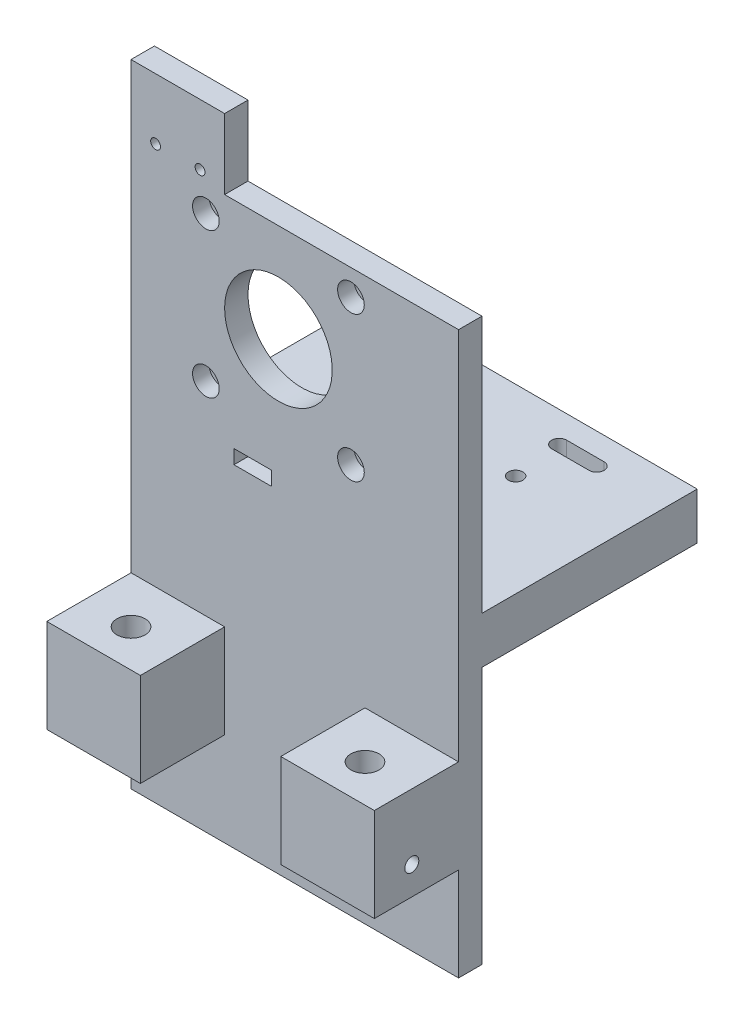
SolidWorks part; units mm, degrees
ref_plane "Front" through (0, 0, 0) normal (0, 0, 1) x (1, 0, 0)
ref_plane "Top" through (0, 0, 0) normal (0, 1, 0) x (1, 0, 0)
ref_plane "Right" through (0, 0, 0) normal (1, 0, 0) x (0, 0, -1)
sketch "Sketch1" plane through (0, 0, 0) normal (0, 0, 1) x (1, 0, 0)
  line L1 (-35, -60) -> (35, -60)
  line L2 (-35, -60) -> (-35, 60)
  line L3 (-35, 60) -> (35, 60)
  line L4 (35, -60) -> (35, 60)
  line L5 (-35, -60) -> (35, 60) construction
  line L6 (-35, 60) -> (35, -60) construction
  point P0 (0, 0)
  dimension "D1" = 120
  dimension "D2" = 70
extrude "Boss-Extrude1" add sketch "Sketch1" along normal blind 5
sketch "Sketch2" plane through (0, 0, 5) normal (0, 0, 1) x (1, 0, 0)
  line L0 (-35, 60) -> (-35, -60) construction
  line L1 (-35, -20) -> (-15, -20)
  line L2 (-35, -20) -> (-35, -40)
  line L3 (-35, -40) -> (-15, -40)
  line L4 (-15, -20) -> (-15, -40)
  line L5 (-35, -20) -> (-15, -40) construction
  line L6 (-35, -40) -> (-15, -20) construction
  line L7 (35, -60) -> (35, 60) construction
  line L8 (35, -20) -> (15, -20)
  line L9 (35, -20) -> (35, -40)
  line L10 (35, -40) -> (15, -40)
  line L11 (15, -20) -> (15, -40)
  line L12 (35, -20) -> (15, -40) construction
  line L13 (35, -40) -> (15, -20) construction
  point P4 (-25, -30)
  point P11 (25, -30)
  dimension "D1" = 20
  dimension "D2" = 20
  dimension "D3" = 20
  dimension "D4" = 20
  dimension "D5" = 40
extrude "Boss-Extrude2" add sketch "Sketch2" along normal blind 18
sketch "Sketch3" plane through (0, -20, 0) normal (0, 1, 0) x (1, 0, 0)
  line L0 (-25, -23) -> (-25, -5) construction
  line L1 (-15, -23) -> (-35, -23) construction
  line L2 (-15, -5) -> (-35, -5) construction
  line L3 (25, -23) -> (25, -5) construction
  line L4 (35, -23) -> (15, -23) construction
  line L5 (35, -5) -> (15, -5) construction
  circle A0 centre (-25, -15) radius 3
  circle A1 centre (25, -15) radius 3
  dimension "D1" = 6
  dimension "D2" = 6
  dimension "D3" = 10
  dimension "D4" = 10
extrude "Cut-Extrude1" cut sketch "Sketch3" against normal up to next
sketch "Sketch4" plane through (0, 0, 0) normal (0, 0, -1) x (-1, 0, 0)
  line L0 (-35, 60) -> (35, 60) construction
  line L1 (-12, 23.5) -> (19, 23.5) construction
  line L2 (-12, 23.5) -> (-12, 54.5) construction
  line L3 (-12, 54.5) -> (19, 54.5) construction
  line L4 (19, 23.5) -> (19, 54.5) construction
  line L5 (-12, 23.5) -> (19, 54.5) construction
  line L6 (-12, 54.5) -> (19, 23.5) construction
  line L7 (35, 60) -> (35, -60) construction
  circle A0 centre (3.5, 39) radius 11.5
  circle A1 centre (-12, 54.5) radius 1.55
  circle A2 centre (19, 54.5) radius 1.55
  circle A3 centre (19, 23.5) radius 1.55
  circle A4 centre (-12, 23.5) radius 1.55
  dimension "D1" = 23
  dimension "D3" = 3.1
  dimension "D4" = 3.1
  dimension "D5" = 3.1
  dimension "D6" = 3.1
  dimension "D2" = 31
  dimension "D7" = 21
  dimension "D8" = 31.5
extrude "Cut-Extrude2" cut sketch "Sketch4" against normal up to next
sketch "Sketch5" plane through (0, 0, 0) normal (0, 0, -1) x (-1, 0, 0)
  line L1 (35, 60) -> (15, 60)
  line L2 (35, 60) -> (35, 75)
  line L3 (35, 75) -> (15, 75)
  line L4 (15, 60) -> (15, 75)
  line L5 (35, 60) -> (15, 75) construction
  line L6 (35, 75) -> (15, 60) construction
  circle A0 centre (20.25, 62) radius 1.05
  circle A1 centre (29.75, 62) radius 1.05
  point P4 (25, 67.5)
  dimension "D3" = 2.1
  dimension "D4" = 2.1
  dimension "D5" = 9.5
  dimension "D7" = 13
  dimension "D1" = 15
  dimension "D2" = 20
  dimension "D6" = 5.25
extrude "Boss-Extrude3" add sketch "Sketch5" against normal up to surface (5 mm away) up to face at (10.45, 23.5, 5)
sketch "Sketch6" plane through (0, 0, 0) normal (0, 0, -1) x (-1, 0, 0)
  line L0 (-35, -60) -> (-35, 60) construction
  line L1 (-35, 5) -> (35, 5)
  line L2 (-35, 5) -> (-35, -5)
  line L3 (-35, -5) -> (35, -5)
  line L4 (35, 5) -> (35, -5)
  line L5 (-35, 5) -> (35, -5) construction
  line L6 (-35, -5) -> (35, 5) construction
  line L7 (35, 75) -> (35, -60) construction
  line L8 (35, -60) -> (-35, -60) construction
  point P4 (0, 0)
  dimension "D1" = 10
  dimension "D2" = 55
extrude "Boss-Extrude4" add sketch "Sketch6" along normal blind 46
sketch "Sketch7" plane through (0, -40, 0) normal (0, 1, 0) x (1, 0, 0)
  line L0 (35, -23) -> (35, -5) construction
  line L1 (29.4, -17.85) -> (32, -17.85)
  line L2 (29.4, -17.85) -> (29.4, -12.15)
  line L3 (29.4, -12.15) -> (32, -12.15)
  line L4 (32, -17.85) -> (32, -12.15)
  line L5 (29.4, -17.85) -> (32, -12.15) construction
  line L6 (29.4, -12.15) -> (32, -17.85) construction
  line L8 (-32, -17.85) -> (-29.4, -17.85)
  line L9 (-32, -17.85) -> (-32, -12.15)
  line L10 (-32, -12.15) -> (-29.4, -12.15)
  line L11 (-29.4, -17.85) -> (-29.4, -12.15)
  line L12 (-32, -17.85) -> (-29.4, -12.15) construction
  line L13 (-32, -12.15) -> (-29.4, -17.85) construction
  line L14 (-35, -23) -> (-35, -5) construction
  line L15 (-25, -15) -> (-30.7, -15) construction
  point P0 (30.7, -15)
  point P5 (-30.7, -15)
  dimension "D1" = 5.7
  dimension "D2" = 2.6
  dimension "D3" = 3
  dimension "D4" = 5.7
  dimension "D5" = 2.6
  dimension "D7" = 3
extrude "Cut-Extrude3" cut sketch "Sketch7" along normal blind 10
sketch "Sketch8" plane through (35, 0, 0) normal (1, 0, 0) x (0, 0, -1)
  line L0 (-23, -40) -> (-23, -20) construction
  line L2 (-23, -40) -> (-5, -40) construction
  circle A0 centre (-15, -34) radius 1.5
  dimension "D1" = 3
  dimension "D3" = 6
  dimension "D2" = 8
extrude "Cut-Extrude4" cut sketch "Sketch8" against normal blind 8
sketch "Sketch9" plane through (-35, 0, 0) normal (-1, 0, 0) x (0, 0, 1)
  circle A0 centre (15, -34) radius 1.5 construction
  circle A1 centre (15, -34) radius 1.5
extrude "Cut-Extrude5" cut sketch "Sketch9" against normal blind 8
sketch "Sketch10" plane through (0, 0, 5) normal (0, 0, 1) x (1, 0, 0)
  circle A0 centre (-19, 54.5) radius 2.85
  circle A1 centre (12, 54.5) radius 2.85
  circle A2 centre (12, 23.5) radius 2.85
  circle A3 centre (-19, 23.5) radius 2.85
  dimension "D1" = 5.7
  dimension "D2" = 5.7
  dimension "D3" = 5.7
  dimension "D4" = 5.7
extrude "Cut-Extrude6" cut sketch "Sketch10" against normal blind 3.5
sketch "Sketch11" plane through (0, 5, 0) normal (0, 1, 0) x (1, 0, 0)
  line L1 (13.194, 4) -> (-11.806, 4) construction
  line L2 (13.194, 4) -> (13.194, 29) construction
  line L3 (13.194, 29) -> (-11.806, 29) construction
  line L4 (-11.806, 4) -> (-11.806, 29) construction
  line L5 (13.194, 4) -> (-11.806, 29) construction
  line L6 (13.194, 29) -> (-11.806, 4) construction
  line L7 (-35, 0) -> (35, 0) construction
  circle A0 centre (-11.806, 29) radius 1.55
  circle A1 centre (-11.806, 4) radius 1.55
  circle A2 centre (13.194, 29) radius 1.55
  circle A3 centre (13.194, 4) radius 1.55
  point P0 (0.694, 16.5)
  dimension "D2" = 3.1
  dimension "D3" = 3.1
  dimension "D4" = 3.1
  dimension "D5" = 3.1
  dimension "D1" = 25
  dimension "D6" = 4
extrude "Cut-Extrude7" cut sketch "Sketch11" against normal up to next
sketch "Sketch13" plane through (0, 5, 0) normal (0, 1, 0) x (1, 0, 0)
  line L0 (-20, 39.5) -> (-12, 39.5) construction
  line L1 (-20, 41.1) -> (-12, 41.1)
  line L2 (-20, 37.9) -> (-12, 37.9)
  line L3 (-35, 46) -> (35, 46) construction
  line L4 (-35, 46) -> (-35, 0) construction
  line L5 (0, 46) -> (0, 39.5) construction
  line L6 (20, 39.5) -> (12, 39.5) construction
  line L7 (20, 41.1) -> (12, 41.1)
  line L8 (20, 37.9) -> (12, 37.9)
  arc A0 (-20, 41.1) -> (-20, 37.9) centre (-20, 39.5) ccw
  arc A1 (-12, 37.9) -> (-12, 41.1) centre (-12, 39.5) ccw
  arc A2 (20, 41.1) -> (20, 37.9) centre (20, 39.5) cw
  arc A3 (12, 37.9) -> (12, 41.1) centre (12, 39.5) cw
  point P2 (-16, 39.5)
  point P16 (16, 39.5)
  dimension "D1" = 1.6
  dimension "D2" = 8
  dimension "D3" = 6.5
  dimension "D4" = 15
extrude "Cut-Extrude8" cut sketch "Sketch13" against normal up to next
sketch "Sketch14" plane through (-35, 0, 0) normal (-1, 0, 0) x (0, 0, 1)
  line L1 (0, -5) -> (-8, -5)
  line L2 (0, -5) -> (0, -21)
  line L3 (0, -21) -> (-8, -21)
  line L4 (-8, -5) -> (-8, -21)
  line L5 (0, -5) -> (-8, -21) construction
  line L6 (0, -21) -> (-8, -5) construction
  point P4 (-4, -13)
  dimension "D1" = 16
  dimension "D2" = 8
extrude "Boss-Extrude5" add sketch "Sketch14" against normal blind 4
sketch "Sketch15" plane through (0, 0, 0) normal (0, 0, -1) x (-1, 0, 0)
  line L0 (35, 5) -> (-35, 5) construction
  line L1 (5, 14) -> (13, 14)
  line L2 (5, 14) -> (5, 11)
  line L3 (5, 11) -> (13, 11)
  line L4 (13, 14) -> (13, 11)
  line L5 (5, 14) -> (13, 11) construction
  line L6 (5, 11) -> (13, 14) construction
  line L7 (35, 75) -> (35, 5) construction
  point P0 (9, 12.5)
  dimension "D1" = 3
  dimension "D2" = 8
  dimension "D3" = 6
  dimension "D4" = 26
extrude "Cut-Extrude9" cut sketch "Sketch15" against normal up to next
